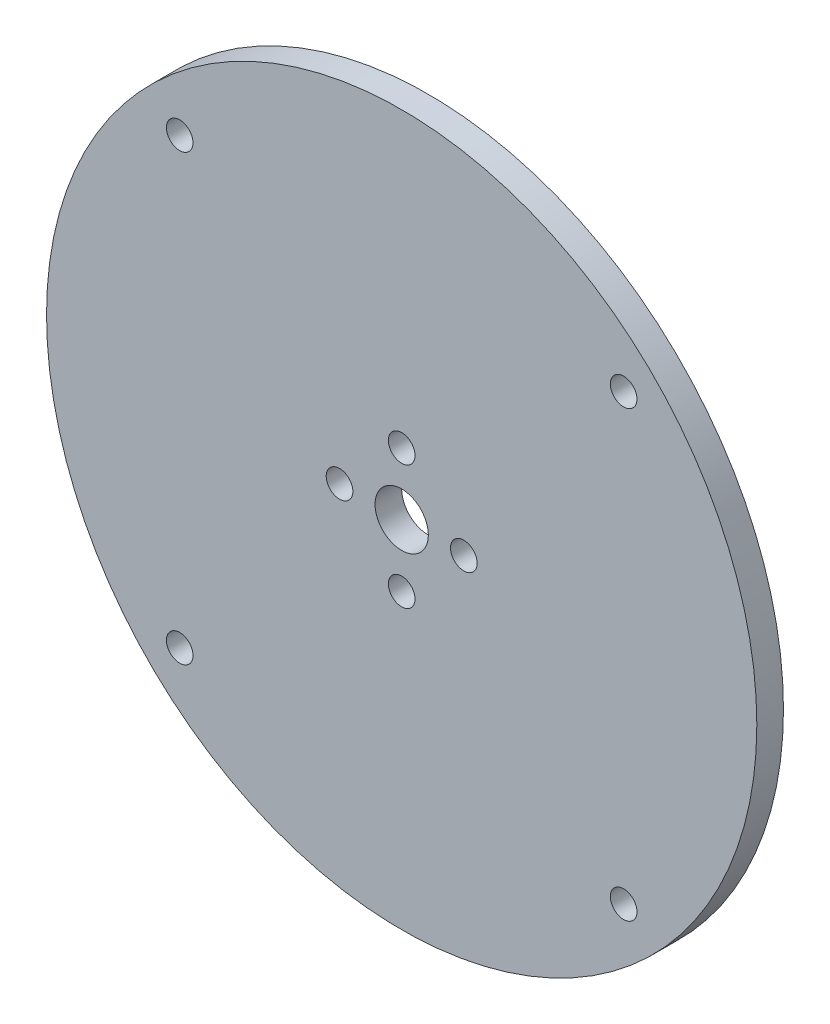
SolidWorks part; units mm, degrees
ref_plane "前视基准面" through (0, 0, 0) normal (0, 0, 1) x (1, 0, 0)
ref_plane "上视基准面" through (0, 0, 0) normal (0, 1, 0) x (1, 0, 0)
ref_plane "右视基准面" through (0, 0, 0) normal (1, 0, 0) x (0, 0, -1)
sketch "草图1" plane through (0, 0, 0) normal (0, 0, 1) x (1, 0, 0)
  line L0 (-25, -25) -> (25, -25)
  line L1 (-25, -25) -> (-25, 25)
  line L2 (-25, 25) -> (25, 25)
  line L3 (25, -25) -> (25, 25)
  line L4 (-25, -25) -> (25, 25) construction
  line L5 (-25, 25) -> (25, -25) construction
  circle A0 centre (0, 0) radius 40
  circle A1 centre (-25, 25) radius 1.5
  circle A2 centre (25, 25) radius 1.5
  circle A3 centre (25, -25) radius 1.5
  circle A4 centre (-25, -25) radius 1.5
  circle A5 centre (0, 0) radius 3
  circle A6 centre (0, 0) radius 7
  circle A7 centre (0, 7) radius 1.5
  circle A8 centre (-7, 0) radius 1.5
  circle A9 centre (7, 0) radius 1.5
  circle A10 centre (0, -7) radius 1.5
  dimension "D2" = 80
  dimension "D4" = 3
  dimension "D5" = 3
  dimension "D6" = 3
  dimension "D7" = 3
  dimension "D8" = 14
  dimension "D9" = 6
  dimension "D10" = 3
  dimension "D11" = 3
  dimension "D12" = 3
  dimension "D13" = 3
  dimension "D1" = 50
  dimension "D3" = 50
extrude "凸台-拉伸1" add sketch "草图1" along normal blind 3 contours A0 A4 L1 A1 L2 A2 L3 A3 L0 | A4 L0 A3 L3 A2 L2 A1 L1 A10 A6 A8 A7 A9 | A10 A6 A9 A7 A8 A5
